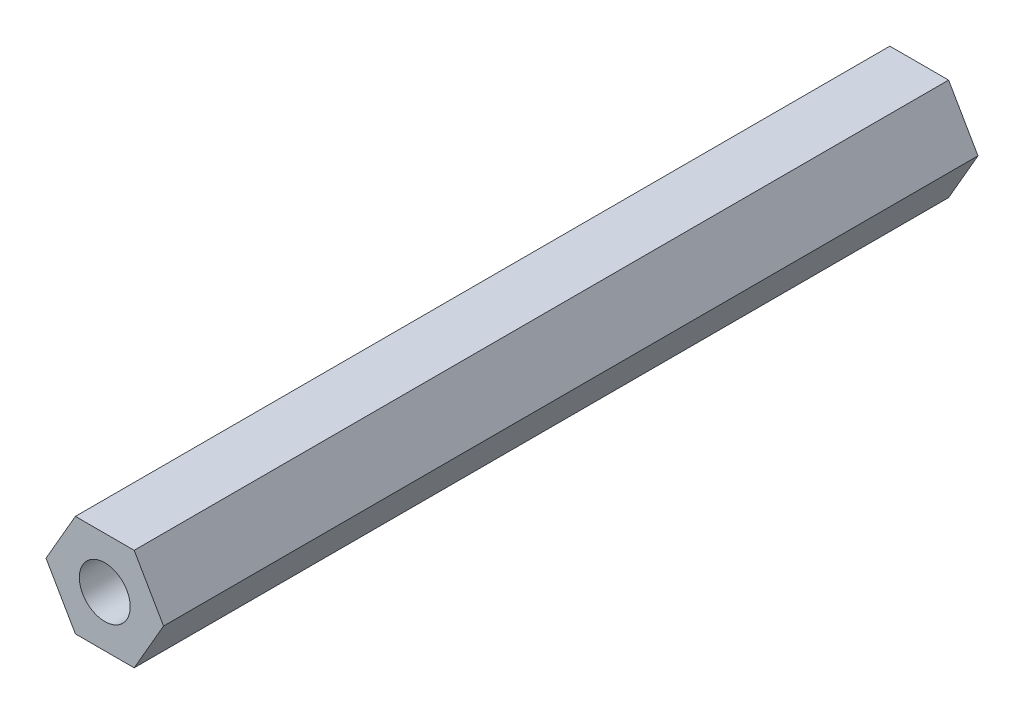
SolidWorks part; units mm, degrees
material "1060 Alloy"
ref_plane "Front Plane" through (0, 0, 0) normal (0, 0, 1) x (1, 0, 0)
ref_plane "Top Plane" through (0, 0, 0) normal (0, 1, 0) x (1, 0, 0)
ref_plane "Right Plane" through (0, 0, 0) normal (1, 0, 0) x (0, 0, -1)
sketch "Sketch1" plane through (0, 0, 0) normal (0, 0, 1) x (1, 0, 0)
  line L1 (3.6662, 6.35) -> (-3.6662, 6.35)
  line L2 (-3.6662, 6.35) -> (-7.3323, 0)
  line L3 (-7.3323, 0) -> (-3.6662, -6.35)
  line L4 (-3.6662, -6.35) -> (3.6662, -6.35)
  line L5 (3.6662, -6.35) -> (7.3323, 0)
  line L6 (7.3323, 0) -> (3.6662, 6.35)
  circle A0 centre (0, 0) radius 6.35 construction
  circle A1 centre (0, 0) radius 3.175
  dimension "D2" = 6.35
  dimension "D1" = 12.7
extrude "Boss-Extrude1" add sketch "Sketch1" along normal mid plane 101.6
